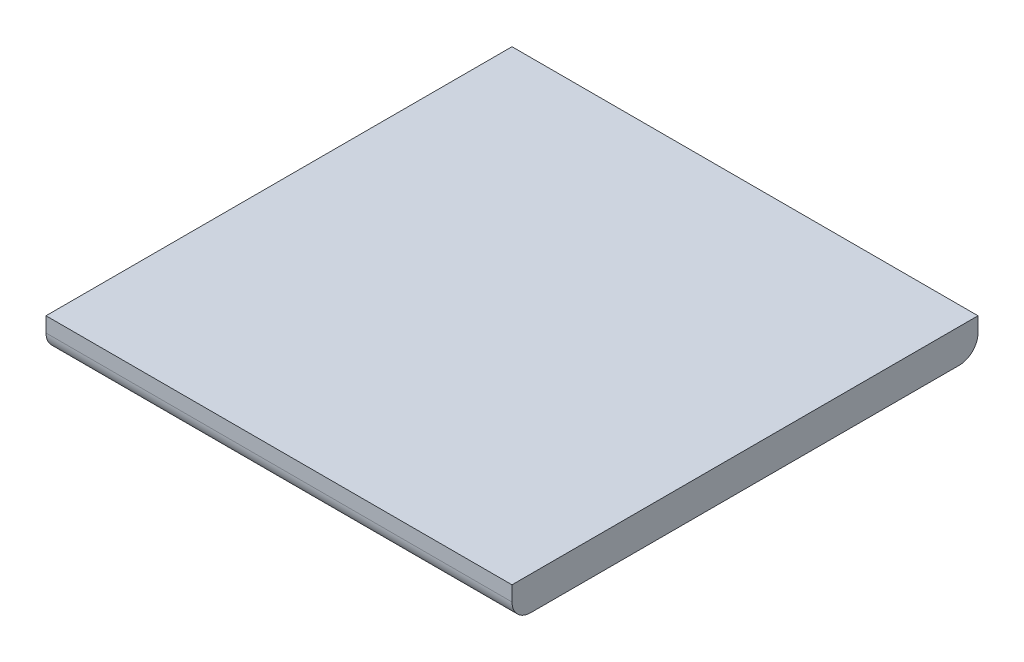
SolidWorks part; units mm, degrees
ref_plane "前视基准面" through (0, 0, 0) normal (0, 0, 1) x (1, 0, 0)
ref_plane "上视基准面" through (0, 0, 0) normal (0, 1, 0) x (1, 0, 0)
ref_plane "右视基准面" through (0, 0, 0) normal (1, 0, 0) x (0, 0, -1)
other "Configuration Table"
sketch "草图1" plane through (0, 0, 0) normal (0, 1, 0) x (1, 0, 0)
  line L1 (-125, -125) -> (125, -125)
  line L2 (-125, -125) -> (-125, 125)
  line L3 (-125, 125) -> (125, 125)
  line L4 (125, -125) -> (125, 125)
  point P4 (-125, 0)
  point P6 (0, 125)
  dimension "D1" = 250
  dimension "D2" = 250
extrude "凸台-拉伸1" add sketch "草图1" along normal blind 18
fillet "圆角1" radius 10 2 edges at (0, 0, 125) (0, 0, -125)
